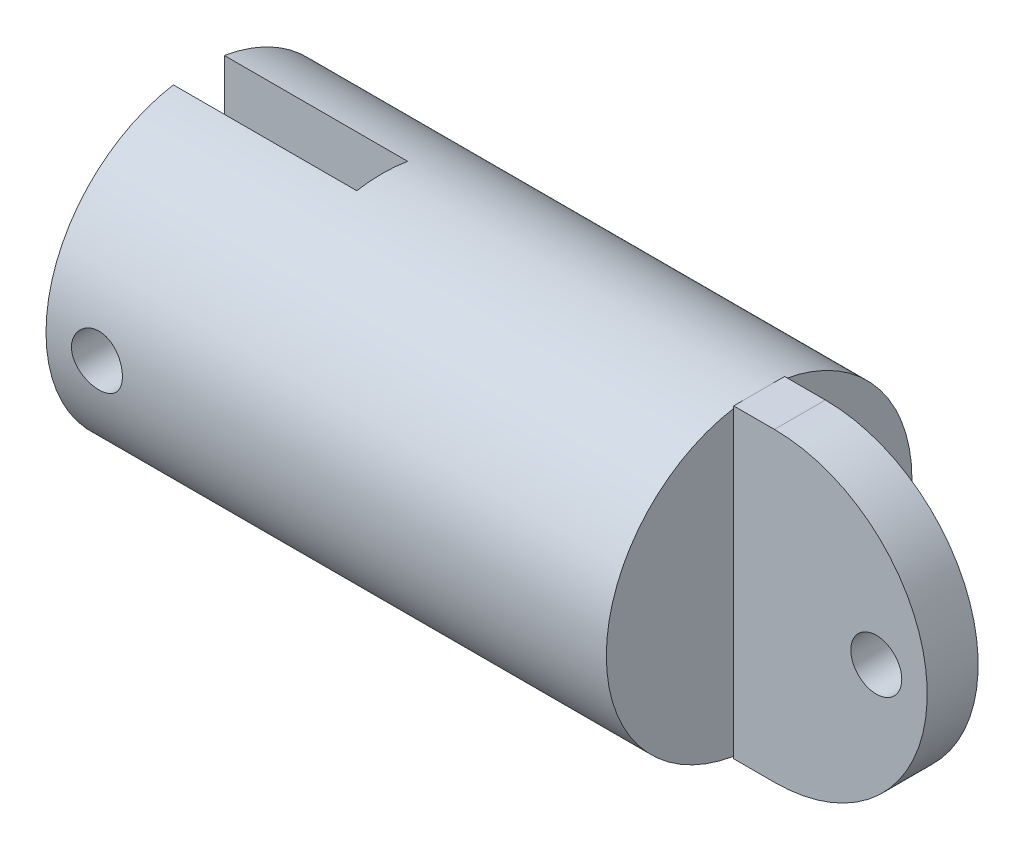
SolidWorks part; units mm, degrees
ref_plane "Front Plane" through (0, 0, 0) normal (0, 0, 1) x (1, 0, 0)
ref_plane "Top Plane" through (0, 0, 0) normal (0, 1, 0) x (1, 0, 0)
ref_plane "Right Plane" through (0, 0, 0) normal (1, 0, 0) x (0, 0, -1)
sketch "Sketch2" plane through (0, 0, 0) normal (1, 0, 0) x (0, 0, -1)
  circle A0 centre (0, 0) radius 15
  dimension "D1" = 30
extrude "Boss-Extrude1" add sketch "Sketch2" against normal blind 55
sketch "Sketch3" plane through (0, 0, 0) normal (0, 1, 0) x (1, 0, 0)
  line L0 (-55, 15) -> (-55, -15) construction
  line L1 (-55, 2.5) -> (-37, 2.5)
  line L2 (-55, 2.5) -> (-55, -2.5)
  line L3 (-55, -2.5) -> (-37, -2.5)
  line L4 (-37, 2.5) -> (-37, -2.5)
  line L5 (0, 15) -> (-55, 15) construction
  dimension "D1" = 5
  dimension "D2" = 18
  dimension "D3" = 0
  dimension "D4" = 12.5
extrude "Cut-Extrude1" cut sketch "Sketch3" against normal through all and the other way through all
sketch "Sketch6" plane through (0, 0, 0) normal (0, 0, 1) x (1, 0, 0)
  line L0 (-55, 14.7902) -> (-55, -14.7902) construction
  circle A0 centre (-50, 0) radius 2.5
  dimension "D2" = 5
  dimension "D1" = 5
  dimension "D3" = 0
extrude "Cut-Extrude2" cut sketch "Sketch6" against normal through all and the other way through all
sketch "Sketch7" plane through (0, 0, 0) normal (1, 0, 0) x (0, 0, -1)
  line L0 (-2.5, 15) -> (-2.5, -15)
  line L1 (-2.5, 15) -> (2.5, 15)
  line L2 (-2.5, -15) -> (2.5, -15)
  line L3 (2.5, 15) -> (2.5, -15)
  line L4 (-2.5, 15) -> (2.5, -15) construction
  line L5 (-2.5, -15) -> (2.5, 15) construction
  point P1 (0, 0)
  dimension "D1" = 5
extrude "Boss-Extrude2" add sketch "Sketch7" along normal blind 4
sketch "Sketch8" plane through (0, 0, 2.5) normal (0, 0, 1) x (1, 0, 0)
  line L1 (4, 15) -> (4, -15) construction
  line L2 (4, 15) -> (4, -15)
  arc A1 (4, -15) -> (4, 15) centre (4, 0) ccw
extrude "Boss-Extrude3" add sketch "Sketch8" against normal blind 5
sketch "Sketch9" plane through (0, 0, 2.5) normal (0, 0, 1) x (1, 0, 0)
  circle A0 centre (14, 0) radius 2.5
  arc A1 (4, -15) -> (4, 15) centre (4, 0) ccw construction
  point P2 (0, 0)
  point P6 (0, 0)
  point P7 (19, 0)
  dimension "D1" = 5
  dimension "D2" = 5
extrude "Cut-Extrude3" cut sketch "Sketch9" against normal through all and the other way through all
